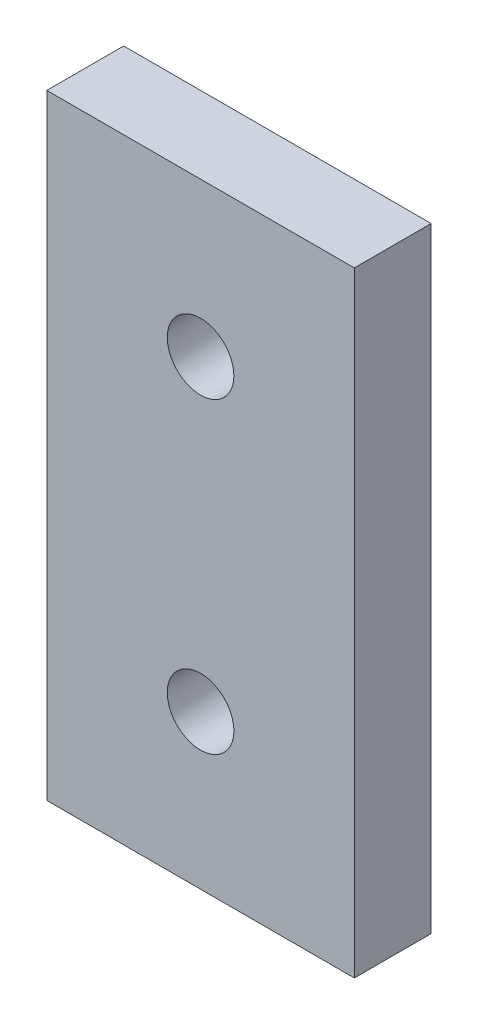
SolidWorks part; units mm, degrees
material "Pin"
ref_plane "Front" through (0, 0, 0) normal (0, 0, 1) x (1, 0, 0)
ref_plane "Top" through (0, 0, 0) normal (0, 1, 0) x (1, 0, 0)
ref_plane "Right" through (0, 0, 0) normal (1, 0, 0) x (0, 0, -1)
sketch "Esquisse1" plane through (0, 0, 0) normal (0, 0, 1) x (1, 0, 0)
  line L1 (-12.7, 25.4) -> (12.7, 25.4)
  line L2 (-12.7, 25.4) -> (-12.7, -25.4)
  line L3 (-12.7, -25.4) -> (12.7, -25.4)
  line L4 (12.7, 25.4) -> (12.7, -25.4)
  line L5 (-12.7, 25.4) -> (12.7, -25.4) construction
  line L6 (-12.7, -25.4) -> (12.7, 25.4) construction
  point P0 (0, 0)
  dimension "D1" = 25.4
  dimension "D2" = 50.8
extrude "Boss.-Extru.1" add sketch "Esquisse1" along normal blind 6.35
sketch "Esquisse2" plane through (0, 0, 6.35) normal (0, 0, 1) x (1, 0, 0)
  line L0 (50, 0) -> (-50, 0) construction
  circle A0 centre (0, 12.7) radius 2.75
  circle A1 centre (0, -12.7) radius 2.75
  point P2 (0, 15.009)
  point P3 (0, 0)
  dimension "D1" = 5.5
  dimension "D2" = 12.7
extrude "Enlèv. mat.-Extru.1" cut sketch "Esquisse2" against normal blind 6.35
